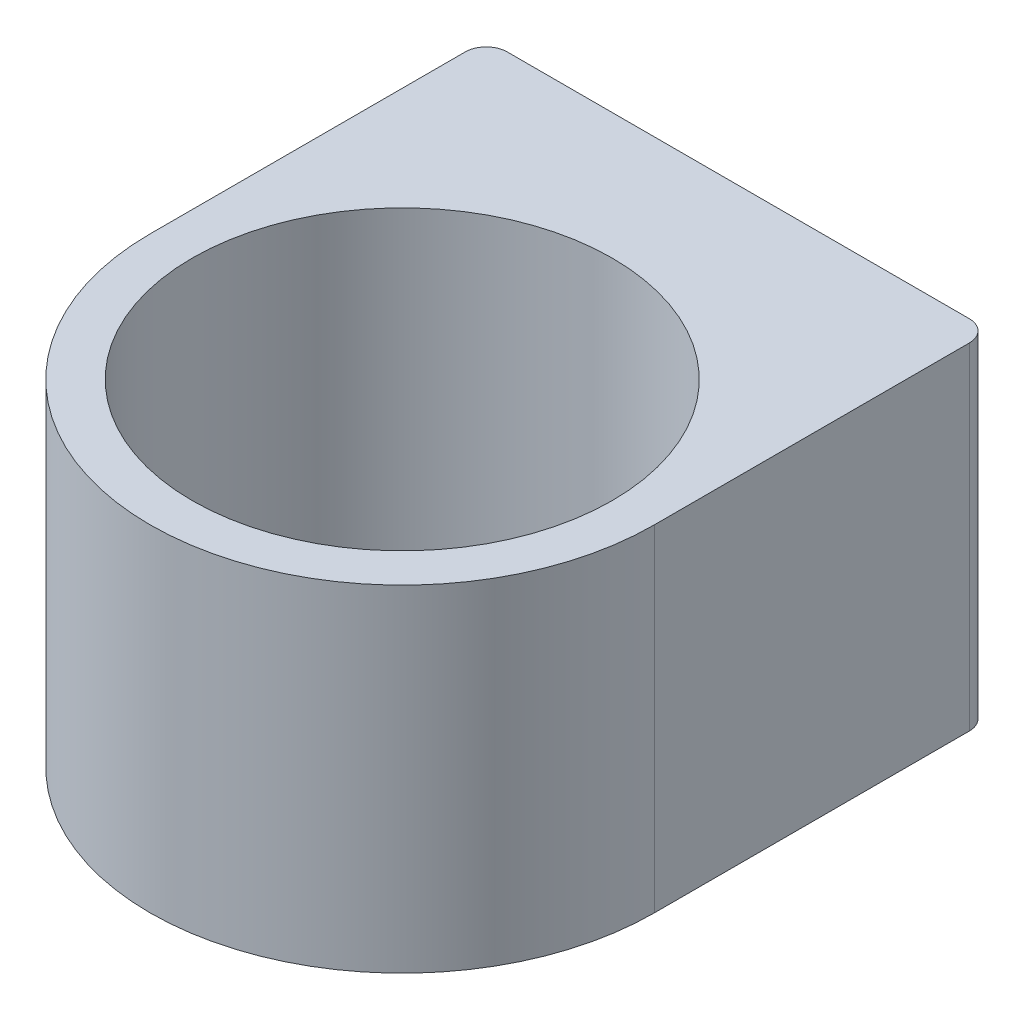
SolidWorks part; units mm, degrees
ref_plane "Front Plane" through (0, 0, 0) normal (0, 0, 1) x (1, 0, 0)
ref_plane "Top Plane" through (0, 0, 0) normal (0, 1, 0) x (1, 0, 0)
ref_plane "Right Plane" through (0, 0, 0) normal (1, 0, 0) x (0, 0, -1)
sketch "Sketch1" plane through (0, 0, 0) normal (0, 1, 0) x (1, 0, 0)
  line L0 (-60, 0) -> (-60, 80)
  line L1 (-60, 80) -> (60, 80)
  line L2 (60, 80) -> (60, 0)
  circle A0 centre (0, 0) radius 50
  arc A1 (-60, 0) -> (60, 0) centre (0, 0) ccw
  circle A2 centre (0, 0) radius 60 construction
  dimension "D1" = 100
  dimension "D3" = 80
  dimension "D2" = 10
extrude "Boss-Extrude1" add sketch "Sketch1" along normal mid plane 80
fillet "Fillet1" radius 5 2 edges at (-60, 0, -80) (60, 0, -80)
sketch "Sketch2" plane through (0, 0, -80) normal (0, 0, -1) x (-1, 0, 0)
  circle A0 centre (0, 0) radius 20
  dimension "D1" = 40
extrude "Boss-Extrude2" add sketch "Sketch2" along normal blind 20
sketch "Sketch7" plane through (0, 0, -100) normal (0, 0, -1) x (-1, 0, 0)
  circle A0 centre (0, 0) radius 16.5
  dimension "D1" = 33
extrude "Cut-Extrude1" cut sketch "Sketch7" against normal up to surface (20 mm away) up to face at (20, 0, -80)
